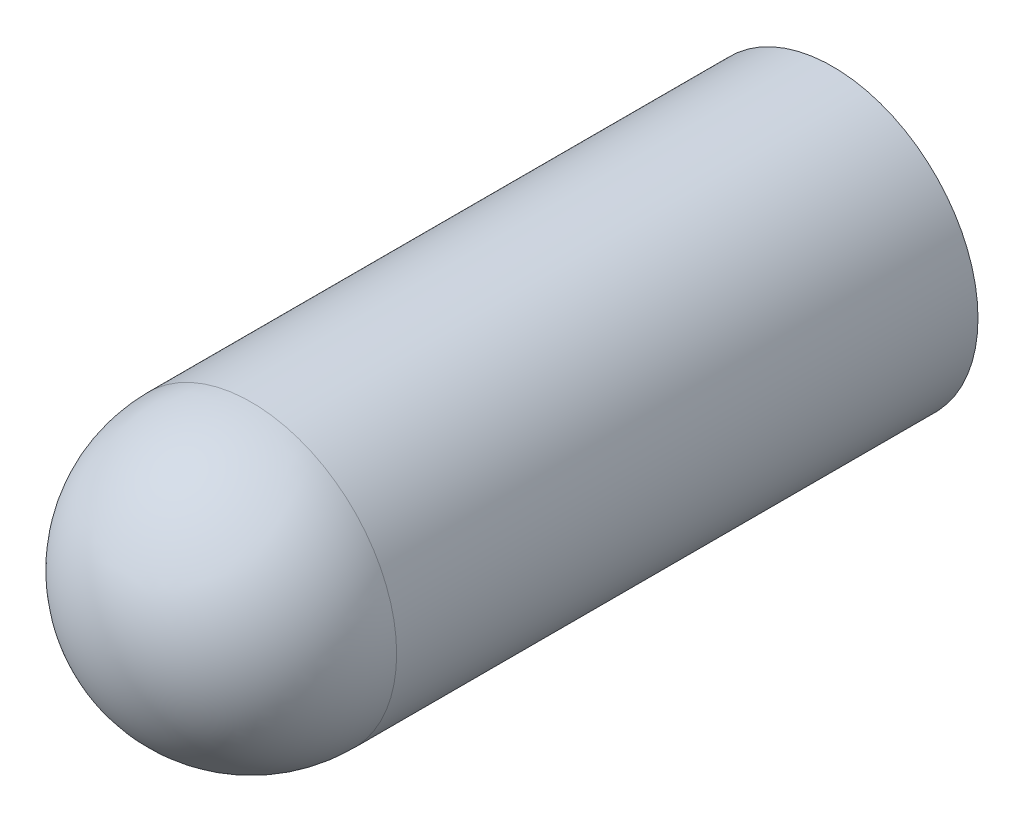
SolidWorks part; units mm, degrees
ref_plane "前视基准面" through (0, 0, 0) normal (0, 0, 1) x (1, 0, 0)
ref_plane "上视基准面" through (0, 0, 0) normal (0, 1, 0) x (1, 0, 0)
ref_plane "右视基准面" through (0, 0, 0) normal (1, 0, 0) x (0, 0, -1)
sketch "草图1" plane through (0, 0, 0) normal (0, 0, 1) x (1, 0, 0)
  circle A0 centre (0, 0) radius 12.5
  dimension "D1" = 25
extrude "凸台-拉伸1" add sketch "草图1" along normal blind 62.5
fillet "圆角1" radius 12.5 1 edges at (12.5, 0, 62.5)
sketch "草图2" plane through (0, 0, 0) normal (0, 0, -1) x (-1, 0, 0)
  circle A0 centre (0, 0) radius 10
  dimension "D1" = 20
extrude "切除-拉伸1" cut sketch "草图2" against normal blind 45 and the other way through all
sketch "草图3" plane through (0, 0, 45) normal (0, 0, -1) x (-1, 0, 0)
  circle A0 centre (0, 0) radius 10.5
  dimension "D1" = 21
extrude "切除-拉伸2" cut sketch "草图3" against normal blind 5
